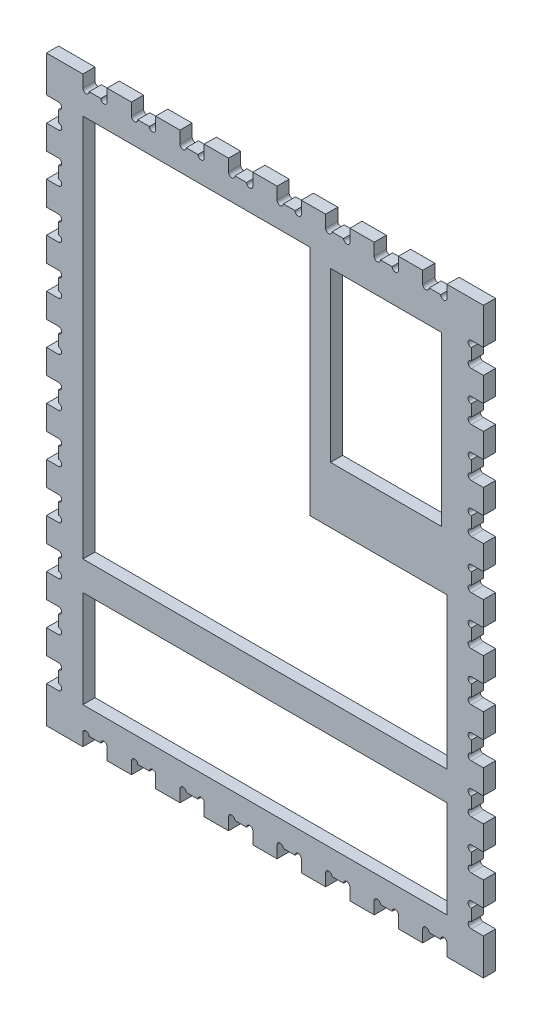
SolidWorks part; units mm, degrees
ref_plane "Front Plane" through (0, 0, 0) normal (0, 0, 1) x (1, 0, 0)
ref_plane "Top Plane" through (0, 0, 0) normal (0, 1, 0) x (1, 0, 0)
ref_plane "Right Plane" through (0, 0, 0) normal (1, 0, 0) x (0, 0, -1)
sketch "Sketch1" plane through (0, 0, 0) normal (0, 0, 1) x (1, 0, 0)
  line L1 (228.6, -304.8) -> (-228.6, -304.8)
  line L2 (228.6, -304.8) -> (228.6, 304.8)
  line L3 (228.6, 304.8) -> (-228.6, 304.8)
  line L4 (-228.6, -304.8) -> (-228.6, 304.8)
  line L5 (228.6, -304.8) -> (-228.6, 304.8) construction
  line L6 (228.6, 304.8) -> (-228.6, -304.8) construction
  line L9 (-203.2, 304.8) -> (-228.6, 304.8) construction
  point P0 (0, 0)
  dimension "D1" = 457.2
  dimension "D2" = 609.6
extrude "Boss-Extrude1" add sketch "Sketch1" along normal blind 12.7
sketch "Sketch2" plane through (0, 0, 12.7) normal (0, 0, 1) x (1, 0, 0)
  line L0 (228.6, 304.8) -> (-228.6, 304.8) construction
  line L1 (-190.5, 292.1) -> (-228.6, 292.1) construction
  line L2 (-190.5, 304.8) -> (-165.1, 304.8)
  line L3 (-190.5, 304.8) -> (-190.5, 292.1)
  line L4 (-190.5, 292.1) -> (-165.1, 292.1)
  line L5 (-165.1, 304.8) -> (-165.1, 292.1)
  line L6 (-228.6, 304.8) -> (-228.6, -304.8) construction
  circle A0 centre (-187.198, 292.1) radius 3.302
  circle A1 centre (-168.402, 292.1) radius 3.302
  line M10 (228.6, 304.8) -> (-228.6, 304.8)
  dimension "D4" = 6.604
  dimension "D5" = 6.604
  dimension "D1" = 25.4
  dimension "D2" = 12.7
  dimension "D3" = 38.1
extrude "Cut-Extrude1" cut sketch "Sketch2" against normal through all contours A1 L5 L3 A0 L4 M10 | L4 A0 | L4 A0 | L4 A1 | L4 A1
pattern_linear "LPattern1" count 8 spacing 50.8 along (1, 0, 0) of "Cut-Extrude1"
sketch "Sketch3" plane through (0, 0, 12.7) normal (0, 0, 1) x (1, 0, 0)
  line L0 (-228.6, 304.8) -> (-228.6, -304.8) construction
  line L1 (-228.6, 266.7) -> (-215.9, 266.7)
  line L2 (-228.6, 266.7) -> (-228.6, 241.3)
  line L3 (-228.6, 241.3) -> (-215.9, 241.3)
  line L4 (-215.9, 266.7) -> (-215.9, 241.3)
  line L5 (-215.9, 266.7) -> (-215.9, 304.8) construction
  line L7 (-190.5, 304.8) -> (-228.6, 304.8) construction
  circle A0 centre (-215.9, 263.398) radius 3.302
  circle A1 centre (-215.9, 244.602) radius 3.302
  dimension "D3" = 6.604
  dimension "D4" = 6.604
  dimension "D1" = 25.4
  dimension "D2" = 12.7
  dimension "D5" = 38.1
extrude "Cut-Extrude2" cut sketch "Sketch3" against normal through all contours A1 L4 A0 L1 L2 L3 | L4 A0 | L4 A1 | L4 A1 | L4 A0
pattern_linear "LPattern2" count 11 spacing 50.8 along (0, -1, 0) of "Cut-Extrude2"
ref_plane "Plane1" through (0, 0, 0) normal (1, 0, 0) x (0, 0, -1)
ref_plane "Plane2" through (0, 0, 0) normal (0, 1, 0) x (1, 0, 0)
mirror "Mirror1" about plane through (0, 0, 0) normal (1, 0, 0) of "LPattern2", "Cut-Extrude2"
mirror "Mirror2" about plane through (0, 0, 0) normal (0, 1, 0) of "LPattern1", "Cut-Extrude1"
sketch "Sketch4" plane through (0, 0, 0) normal (0, 0, -1) x (-1, 0, 0)
  line L0 (-191.5193, 277.7446) -> (-191.5193, 53.4626) construction
  line L9 (190.5, -266.7) -> (-190.5, -266.7)
  line L10 (190.5, -266.7) -> (190.5, -165.1)
  line L11 (190.5, -165.1) -> (-190.5, -165.1)
  line L12 (-190.5, -266.7) -> (-190.5, -165.1)
  line L13 (-191.5193, 53.4626) -> (-59.4393, 53.4626) construction
  line L14 (-59.4393, 53.4626) -> (-59.4393, 277.7446) construction
  line L15 (-59.4393, 277.7446) -> (-191.5193, 277.7446) construction
  line L16 (0, -266.7) -> (0, -304.8) construction
  line L17 (12.7, -304.8) -> (-12.7, -304.8) construction
  line L20 (-190.5, -134.6484) -> (190.5, -134.6484)
  line L21 (190.5, -134.6484) -> (190.5, 266.7)
  line L22 (190.5, 266.7) -> (-47.2777, 266.7)
  line L23 (-47.2777, 266.7) -> (-47.2777, 23.368)
  line L24 (-47.2777, 23.368) -> (-190.5, 23.368)
  line L25 (-190.5, 23.368) -> (-190.5, -134.6484)
  line L26 (190.5, -266.7) -> (215.9, -266.7) construction
  line L27 (-184.9346, 258.2707) -> (-68.6074, 82.4497) construction
  line L28 (-184.9346, 258.2707) -> (-68.6074, 258.2707)
  line L29 (-184.9346, 258.2707) -> (-184.9346, 82.4497)
  line L30 (-184.9346, 82.4497) -> (-68.6074, 82.4497)
  line L31 (-68.6074, 258.2707) -> (-68.6074, 82.4497)
  line L33 (190.5, 292.1) -> (190.5, 266.7)
  line L34 (215.9, 266.7) -> (190.5, 266.7) construction
  line L37 (-190.5, -134.6484) -> (-190.5, -165.1) construction
  line L38 (190.5, -134.6484) -> (190.5, -165.1) construction
  point P4 (0, 0)
  dimension "D2" = 210.82
  dimension "D3" = 101.6
  dimension "D6" = 224.282
  dimension "D7" = 132.08
extrude "Cut-Extrude3" cut sketch "Sketch4" against normal through all contours L31 L28 L29 L30 | L24 L25 L20 L21 L22 L23 | L12 L9 L10 L11
